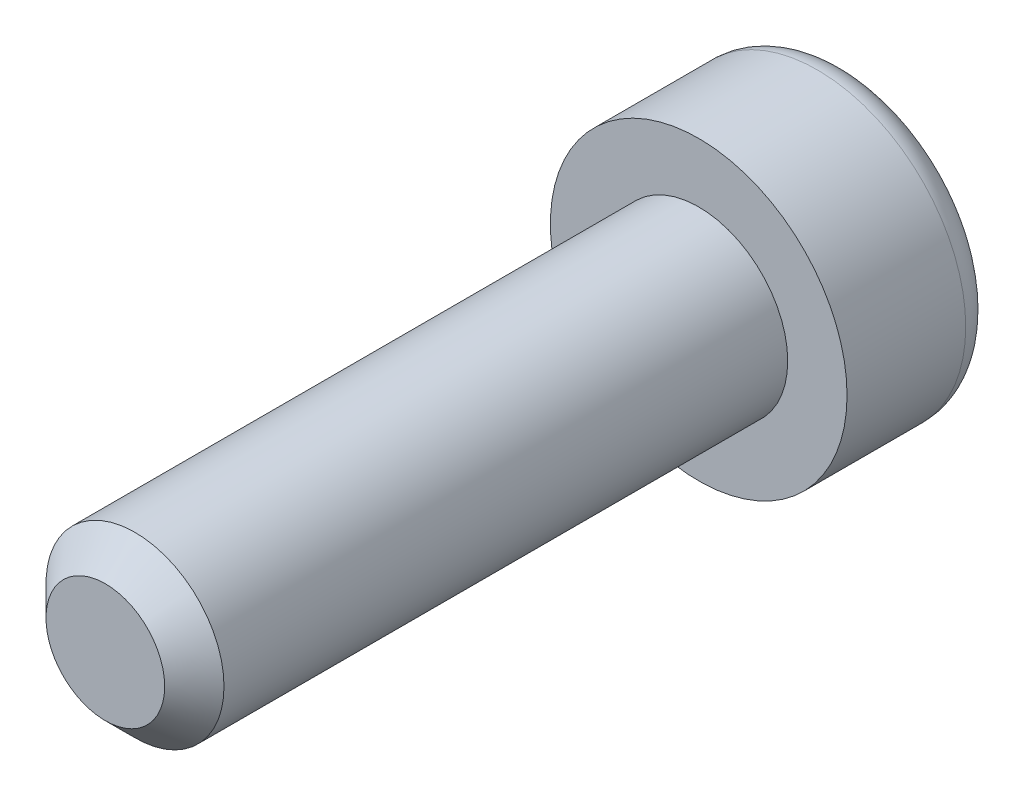
SolidWorks part; units mm, degrees
ref_plane "Plan1" through (0, 0, 0) normal (0, 0, 1) x (1, 0, 0)
ref_plane "Plan2" through (0, 0, 0) normal (0, 1, 0) x (1, 0, 0)
ref_plane "Plan3" through (0, 0, 0) normal (1, 0, 0) x (0, 0, -1)
sketch "Esquisse1" plane through (0, 0, 0) normal (0, 0, 1) x (1, 0, 0)
  circle A0 centre (0, 0) radius 2.5
  dimension "D1" = 5
extrude "Base-Extrusion" add sketch "Esquisse1" along normal blind 2.5
sketch "Esquisse2" plane through (0, 0, 2.5) normal (0, 0, 1) x (1, 0, 0)
  circle A0 centre (0, 0) radius 1.5
  dimension "D1" = 3
extrude "Boss.-Extru.1" add sketch "Esquisse2" along normal blind 10
sketch "Esquisse3" plane through (0, 0, 0) normal (0, 0, -1) x (-1, 0, 0)
  line L0 (0, 3) -> (0, -3) construction
  line L1 (0, 1.45) -> (-1.25, 0.7283)
  line L2 (0, 1.45) -> (1.25, 0.7283)
  line L3 (-1.25, 0.7283) -> (-1.25, -0.7151)
  line L4 (1.25, 0.7283) -> (1.25, -0.7151)
  line L5 (-1.25, -0.7151) -> (0, -1.4368)
  line L6 (1.25, -0.7151) -> (0, -1.4368)
  line L7 (-2, 0) -> (2, 0) construction
  dimension "D1" = 2.5
  dimension "D2" = 2.5
  dimension "D3" = 60
  dimension "D4" = 1.45
extrude "Enlèv. mat.-Extru.1" cut sketch "Esquisse3" against normal blind 2
fillet "Congé1" radius 0.5 1 edges at (2.5, 0, 0)
chamfer "Chanfrein1" distance 0.5 angle 45 1 edges at (1.5, 0, 12.5)
